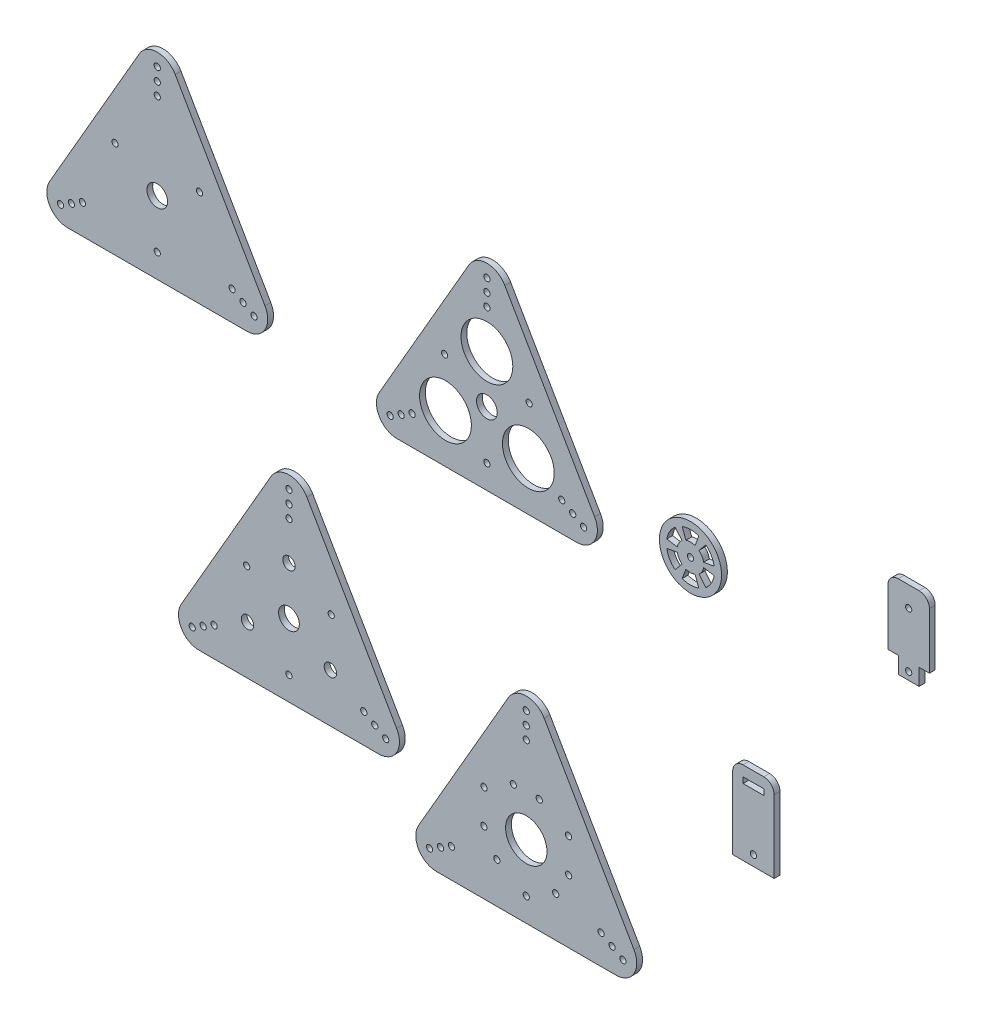
SolidWorks part; units mm, degrees
ref_plane "Front Plane" through (0, 0, 0) normal (0, 0, 1) x (1, 0, 0)
ref_plane "Top Plane" through (0, 0, 0) normal (0, 1, 0) x (1, 0, 0)
ref_plane "Right Plane" through (0, 0, 0) normal (1, 0, 0) x (0, 0, -1)
sketch "wheel" plane through (0, 0, 0) normal (0, 0, 1) x (1, 0, 0)
  line L36 (294.0163, 151.0941) -> (304.0163, 151.0941)
  line L37 (309.0163, 146.0941) -> (309.0163, 119.0941)
  line L38 (289.0163, 119.0941) -> (289.0163, 146.0941)
  line L39 (299.0163, 111.0941) -> (294.0163, 111.0941)
  line L40 (299.0163, 111.0941) -> (304.0163, 111.0941)
  line L41 (294.0163, 119.0941) -> (289.0163, 119.0941)
  line L42 (304.0163, 119.0941) -> (309.0163, 119.0941)
  line L43 (304.0163, 111.0941) -> (304.0163, 119.0941)
  line L44 (294.0163, 111.0941) -> (294.0163, 119.0941)
  circle A92 centre (299.0163, 114.7941) radius 1.5
  circle A93 centre (299.0163, 141.2541) radius 1.5
  arc A94 (294.0163, 151.0941) -> (289.0163, 146.0941) centre (294.0163, 146.0941) ccw
  arc A95 (309.0163, 146.0941) -> (304.0163, 151.0941) centre (304.0163, 146.0941) ccw
sketch "Sketch2" plane through (0, 0, 0) normal (0, 0, 1) x (1, 0, 0)
  line L0 (-8.6603, 42.5) -> (-51.9615, -32.5)
  line L1 (-43.3013, -47.5) -> (43.3013, -47.5)
  line L2 (51.9615, -32.5) -> (8.6603, 42.5)
  circle A0 centre (0, -36.045) radius 1.5
  circle A1 centre (20.3906, -0.7275) radius 1.5
  circle A2 centre (-20.3906, -0.7275) radius 1.5
  circle A3 centre (0, 41.3975) radius 1.5
  circle A4 centre (0, 35.295) radius 1.5
  circle A5 centre (0, 29.1925) radius 1.5
  circle A6 centre (-46.6766, -39.4487) radius 1.5
  circle A7 centre (-41.3917, -36.3975) radius 1.5
  circle A8 centre (-36.1068, -33.3462) radius 1.5
  circle A9 centre (46.6766, -39.4487) radius 1.5
  circle A10 centre (41.3917, -36.3975) radius 1.5
  circle A11 centre (36.1068, -33.3463) radius 1.5
  circle A12 centre (0, 10.59) radius 3
  circle A13 centre (-19.9965, -24.045) radius 3
  circle A14 centre (19.9965, -24.045) radius 3
  circle A15 centre (0, -12.5) radius 5
  arc A16 (-51.9615, -32.5) -> (-43.3013, -47.5) centre (-43.3013, -37.5) ccw
  arc A17 (43.3013, -47.5) -> (51.9615, -32.5) centre (43.3013, -37.5) ccw
  arc A18 (8.6603, 42.5) -> (-8.6603, 42.5) centre (0, 37.5) ccw
sketch "Sketch3" plane through (0, 0, 0) normal (0, 0, 1) x (1, 0, 0)
  line L0 (-72.2035, 187.3479) -> (-115.5048, 112.3479)
  line L1 (-106.8445, 97.3479) -> (-20.242, 97.3479)
  line L2 (-11.5817, 112.3479) -> (-54.883, 187.3479)
  circle A0 centre (-63.5432, 108.8029) radius 1.5
  circle A1 centre (-43.1527, 144.1204) radius 1.5
  circle A2 centre (-83.9338, 144.1204) radius 1.5
  circle A3 centre (-63.5432, 186.2454) radius 1.5
  circle A4 centre (-63.5432, 180.1429) radius 1.5
  circle A5 centre (-63.5432, 174.0404) radius 1.5
  circle A6 centre (-110.2199, 105.3992) radius 1.5
  circle A7 centre (-104.9349, 108.4504) radius 1.5
  circle A8 centre (-99.65, 111.5017) radius 1.5
  circle A9 centre (-16.8666, 105.3992) radius 1.5
  circle A10 centre (-22.1516, 108.4504) radius 1.5
  circle A11 centre (-27.4365, 111.5017) radius 1.5
  circle A12 centre (-63.5432, 132.3479) radius 5
  arc A13 (-115.5048, 112.3479) -> (-106.8445, 97.3479) centre (-106.8445, 107.3479) ccw
  arc A14 (-20.242, 97.3479) -> (-11.5817, 112.3479) centre (-20.242, 107.3479) ccw
  arc A15 (-54.883, 187.3479) -> (-72.2035, 187.3479) centre (-63.5432, 182.3479) ccw
sketch "Sketch4" plane through (0, 0, 0) normal (0, 0, 1) x (1, 0, 0)
  line L0 (105.8488, 7.3231) -> (62.5475, -67.6769)
  line L1 (71.2078, -82.6769) -> (157.8103, -82.6769)
  line L2 (166.4706, -67.6769) -> (123.1693, 7.3231)
  circle A0 centre (114.5091, -71.2219) radius 1.5
  circle A1 centre (134.8996, -35.9044) radius 1.5
  circle A2 centre (94.1185, -35.9044) radius 1.5
  circle A3 centre (114.5091, 6.2206) radius 1.5
  circle A4 centre (114.5091, 0.1181) radius 1.5
  circle A5 centre (114.5091, -5.9844) radius 1.5
  circle A6 centre (67.8325, -74.6257) radius 1.5
  circle A7 centre (73.1174, -71.5744) radius 1.5
  circle A8 centre (78.4023, -68.5232) radius 1.5
  circle A9 centre (161.1857, -74.6257) radius 1.5
  circle A10 centre (155.9008, -71.5744) radius 1.5
  circle A11 centre (150.6158, -68.5232) radius 1.5
  circle A12 centre (108.2591, -27.6769) radius 1.5
  circle A13 centre (120.7591, -27.6769) radius 1.5
  circle A14 centre (100.3136, -63.0896) radius 1.5
  circle A15 centre (94.0636, -52.2643) radius 1.5
  circle A16 centre (134.9546, -52.2643) radius 1.5
  circle A17 centre (128.7046, -63.0896) radius 1.5
  circle A18 centre (114.5091, -47.6769) radius 10
  arc A19 (62.5475, -67.6769) -> (71.2078, -82.6769) centre (71.2078, -72.6769) ccw
  arc A20 (157.8103, -82.6769) -> (166.4706, -67.6769) centre (157.8103, -72.6769) ccw
  arc A21 (123.1693, 7.3231) -> (105.8488, 7.3231) centre (114.5091, 2.3231) ccw
sketch "Sketch5" plane through (0, 0, 0) normal (0, 0, 1) x (1, 0, 0)
  line L0 (86.851, 178.6851) -> (43.5497, 103.6851)
  line L1 (52.21, 88.6851) -> (138.8125, 88.6851)
  line L2 (147.4728, 103.6851) -> (104.1715, 178.6851)
  circle A0 centre (95.5113, 146.7751) radius 12.5
  circle A1 centre (75.5147, 112.1401) radius 12.5
  circle A2 centre (115.5078, 112.1401) radius 12.5
  circle A3 centre (95.5113, 100.1401) radius 1.5
  circle A4 centre (115.9018, 135.4576) radius 1.5
  circle A5 centre (75.1207, 135.4576) radius 1.5
  circle A6 centre (95.5113, 177.5826) radius 1.5
  circle A7 centre (95.5113, 171.4801) radius 1.5
  circle A8 centre (95.5113, 165.3776) radius 1.5
  circle A9 centre (48.8347, 96.7364) radius 1.5
  circle A10 centre (54.1196, 99.7876) radius 1.5
  circle A11 centre (59.4045, 102.8389) radius 1.5
  circle A12 centre (142.1879, 96.7364) radius 1.5
  circle A13 centre (136.9029, 99.7876) radius 1.5
  circle A14 centre (131.618, 102.8389) radius 1.5
  circle A15 centre (95.5113, 123.6851) radius 5
  arc A16 (43.5497, 103.6851) -> (52.21, 88.6851) centre (52.21, 98.6851) ccw
  arc A17 (138.8125, 88.6851) -> (147.4728, 103.6851) centre (138.8125, 98.6851) ccw
  arc A18 (104.1715, 178.6851) -> (86.851, 178.6851) centre (95.5113, 173.6851) ccw
sketch "Sketch6" plane through (0, 0, 0) normal (0, 0, 1) x (1, 0, 0)
  line L0 (214.1118, -4.1344) -> (234.1118, -4.1344)
  line L1 (234.1118, -4.1344) -> (234.1118, 30.8656)
  line L2 (229.1118, 35.8656) -> (219.1118, 35.8656)
  line L3 (214.1118, 30.8656) -> (214.1118, -4.1344)
  line L4 (224.1118, 30.8656) -> (219.1118, 30.8656)
  line L5 (219.1118, 30.8656) -> (219.1118, 28.0656)
  line L6 (219.1118, 28.0656) -> (229.1118, 28.0656)
  line L7 (229.1118, 28.0656) -> (229.1118, 30.8656)
  line L8 (229.1118, 30.8656) -> (224.1118, 30.8656)
  arc A0 (219.1118, 35.8656) -> (214.1118, 30.8656) centre (219.1118, 30.8656) ccw
  arc A1 (234.1118, 30.8656) -> (229.1118, 35.8656) centre (229.1118, 30.8656) ccw
  circle A2 centre (224.1118, 0.8656) radius 1.5
sketch "Sketch7" plane through (0, 0, 0) normal (0, 0, 1) x (1, 0, 0)
  line L0 (182.3262, 111.8812) -> (187.415, 110.9997)
  line L1 (182.3257, 107.9278) -> (187.4148, 108.8081)
  line L2 (186.3225, 101.0033) -> (189.6304, 104.9696)
  line L3 (189.7461, 99.0261) -> (191.5282, 103.8735)
  line L4 (197.7412, 99.0252) -> (195.9603, 103.873)
  line L5 (201.1653, 101.0015) -> (197.8584, 104.9686)
  line L6 (205.1637, 107.9251) -> (200.0749, 108.8066)
  line L7 (205.1642, 111.8785) -> (200.0751, 110.9982)
  line L8 (201.1674, 118.803) -> (197.8595, 114.8367)
  line L9 (197.7438, 120.7802) -> (195.9617, 115.9328)
  line L10 (189.7487, 120.7811) -> (191.5296, 115.9333)
  line L11 (186.3246, 118.8048) -> (189.6315, 114.8377)
  circle A0 centre (193.7449, 109.9032) radius 1.5
  circle A1 centre (193.7449, 109.9032) radius 15
  arc A2 (187.4148, 108.8081) -> (189.6304, 104.9696) centre (193.7449, 109.9032) ccw
  arc A3 (191.5282, 103.8735) -> (195.9603, 103.873) centre (193.7449, 109.9032) ccw
  arc A4 (189.7461, 99.0261) -> (197.7412, 99.0252) centre (193.7449, 109.9032) ccw
  arc A5 (182.3257, 107.9278) -> (186.3225, 101.0033) centre (193.7449, 109.9032) ccw
  arc A6 (186.3246, 118.8048) -> (182.3262, 111.8812) centre (193.7449, 109.9032) ccw
  arc A7 (189.6315, 114.8377) -> (187.415, 110.9997) centre (193.7449, 109.9032) ccw
  arc A8 (197.8584, 104.9686) -> (200.0749, 108.8066) centre (193.7449, 109.9032) ccw
  arc A9 (201.1653, 101.0015) -> (205.1637, 107.9251) centre (193.7449, 109.9032) ccw
  arc A10 (205.1642, 111.8785) -> (201.1674, 118.803) centre (193.7449, 109.9032) ccw
  arc A11 (200.0751, 110.9982) -> (197.8595, 114.8367) centre (193.7449, 109.9032) ccw
  arc A12 (197.7438, 120.7802) -> (189.7487, 120.7811) centre (193.7449, 109.9032) ccw
  arc A13 (195.9617, 115.9328) -> (191.5296, 115.9333) centre (193.7449, 109.9032) ccw
extrude "Boss-Extrude1" add sketch "wheel" along normal blind 2.8
extrude "Boss-Extrude2" add sketch "Sketch2" along normal blind 2.8 separate body
extrude "Boss-Extrude3" add sketch "Sketch3" along normal blind 2.8 separate body
extrude "Boss-Extrude4" add sketch "Sketch4" along normal blind 2.8 separate body
extrude "Boss-Extrude5" add sketch "Sketch5" along normal blind 2.8 separate body
extrude "Boss-Extrude6" add sketch "Sketch6" along normal blind 2.8 separate body
extrude "Boss-Extrude7" add sketch "Sketch7" along normal blind 2.8 separate body
